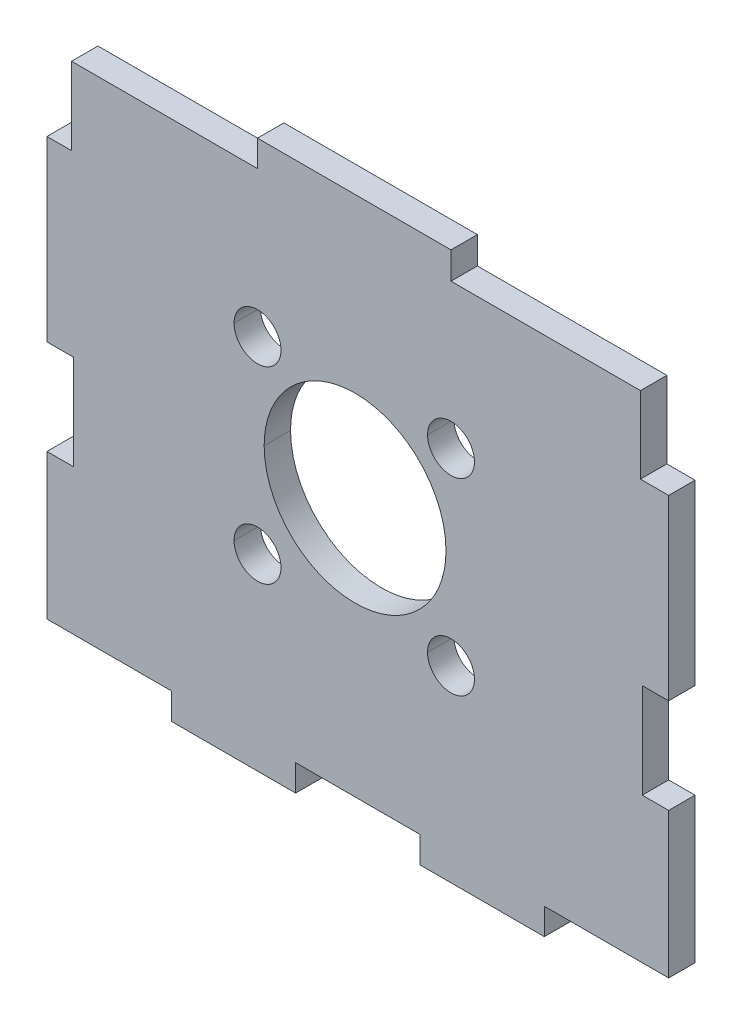
SolidWorks part; units mm, degrees
ref_plane "Front Plane" through (0, 0, 0) normal (0, 0, 1) x (1, 0, 0)
ref_plane "Top Plane" through (0, 0, 0) normal (0, 1, 0) x (1, 0, 0)
ref_plane "Right Plane" through (0, 0, 0) normal (1, 0, 0) x (0, 0, -1)
sketch "Model" plane through (0, 0, 0) normal (0, 0, 1) x (1, 0, 0)
  line L0 (1362.8391, -825.0017) -> (1341.639, -825.0017)
  line L1 (1341.639, -825.0017) -> (1341.639, -829.5017)
  line L2 (1341.639, -829.5017) -> (1320.4393, -829.5017)
  line L3 (1320.4393, -829.5017) -> (1320.4393, -825.0017)
  line L4 (1299.2389, -825.0017) -> (1320.4393, -825.0017)
  line L5 (1358.3392, -800.2518) -> (1358.3392, -784.0763)
  line L6 (1358.3392, -800.2518) -> (1362.8391, -800.2518)
  line L7 (1358.0325, -740.6675) -> (1358.0325, -753.7423)
  line L8 (1261.0324, -753.7423) -> (1261.0324, -740.5377)
  line L10 (1299.2389, -825.0017) -> (1299.2389, -829.5017)
  line L11 (1299.2389, -829.5017) -> (1278.0391, -829.5017)
  line L12 (1278.0391, -829.5017) -> (1278.0391, -825.0017)
  line L13 (1278.0391, -825.0017) -> (1256.8391, -825.0017)
  line L14 (1256.8391, -825.0017) -> (1256.8391, -800.2518)
  line L15 (1256.8391, -800.2518) -> (1261.339, -800.2518)
  line L16 (1261.339, -784.0763) -> (1261.339, -800.2518)
  line L17 (1362.8391, -800.2518) -> (1362.8391, -825.0017)
  line L18 (1292.738, -740.5377) -> (1292.738, -736.0378)
  line L19 (1292.738, -736.0378) -> (1325.7272, -736.0378)
  line L20 (1325.7272, -736.0378) -> (1325.7272, -740.6675)
  line L21 (1292.738, -740.5377) -> (1261.0324, -740.5377)
  line L23 (1261.0324, -753.7423) -> (1256.8391, -753.7423)
  line L24 (1256.8391, -753.7423) -> (1256.8391, -784.0777)
  line L25 (1256.8391, -784.0777) -> (1261.339, -784.0763)
  line L26 (1358.0325, -753.7423) -> (1362.8391, -753.7423)
  line L27 (1362.8391, -753.7423) -> (1362.8391, -784.0763)
  line L28 (1362.8391, -784.0763) -> (1358.3392, -784.0763)
  spline S0 degree 3 poles (1293.8735, -780.8764) (1293.8735, -772.3156) (1300.8122, -765.3762) (1309.3733, -765.3762) (1317.9337, -765.3762) (1324.8735, -772.3156) (1324.8735, -780.8764) knots 2 2 2 2 3 3 3 4 4 4 4
  spline S1 degree 3 poles (1324.8735, -780.8764) (1324.8735, -789.4366) (1317.9337, -796.3762) (1309.3733, -796.3762) (1300.8122, -796.3762) (1293.8735, -789.4366) (1293.8735, -780.8764) knots 0 0 0 0 1 1 1 2 2 2 2
  spline S2 degree 3 poles (1321.7274, -797.4569) (1321.7274, -795.2472) (1323.5185, -793.4565) (1325.7275, -793.4565) (1327.9365, -793.4565) (1329.7273, -795.2472) (1329.7273, -797.4569) knots 2 2 2 2 3 3 3 4 4 4 4
  spline S3 degree 3 poles (1329.7273, -797.4569) (1329.7273, -799.6659) (1327.9365, -801.4567) (1325.7275, -801.4567) (1323.5185, -801.4567) (1321.7274, -799.6659) (1321.7274, -797.4569) knots 0 0 0 0 1 1 1 2 2 2 2
  spline S4 degree 3 poles (1321.7274, -765.3541) (1321.7274, -763.1444) (1323.5185, -761.3537) (1325.7275, -761.3537) (1327.9365, -761.3537) (1329.7273, -763.1444) (1329.7273, -765.3541) knots 2 2 2 2 3 3 3 4 4 4 4
  spline S5 degree 3 poles (1329.7273, -765.3541) (1329.7273, -767.5631) (1327.9365, -769.3539) (1325.7275, -769.3539) (1323.5185, -769.3539) (1321.7274, -767.5631) (1321.7274, -765.3541) knots 0 0 0 0 1 1 1 2 2 2 2
  spline S6 degree 3 poles (1288.7382, -765.3541) (1288.7382, -763.1444) (1290.529, -761.3537) (1292.7383, -761.3537) (1294.9473, -761.3537) (1296.7384, -763.1444) (1296.7384, -765.3541) knots 2 2 2 2 3 3 3 4 4 4 4
  spline S7 degree 3 poles (1296.7384, -765.3541) (1296.7384, -767.5631) (1294.9473, -769.3539) (1292.7383, -769.3539) (1290.529, -769.3539) (1288.7382, -767.5631) (1288.7382, -765.3541) knots 0 0 0 0 1 1 1 2 2 2 2
  spline S8 degree 3 poles (1288.7382, -797.4569) (1288.7382, -795.2472) (1290.529, -793.4565) (1292.7383, -793.4565) (1294.9473, -793.4565) (1296.7384, -795.2472) (1296.7384, -797.4569) knots 2 2 2 2 3 3 3 4 4 4 4
  spline S9 degree 3 poles (1296.7384, -797.4569) (1296.7384, -799.6659) (1294.9473, -801.4567) (1292.7383, -801.4567) (1290.529, -801.4567) (1288.7382, -799.6659) (1288.7382, -797.4569) knots 0 0 0 0 1 1 1 2 2 2 2
  spline S10 degree 2 poles (1325.7272, -740.6675) (1344.5505, -740.6675) (1358.0325, -740.6675) knots 0 0 0 1 1 1
extrude "Boss-Extrude1" add sketch "Model" along normal blind 4.5
